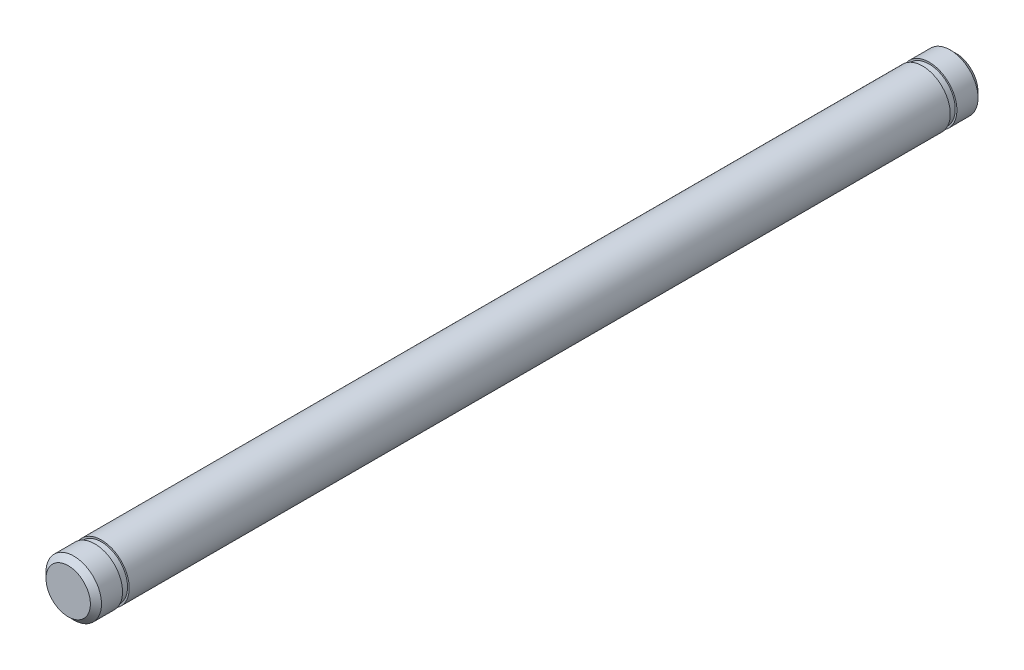
SolidWorks part; units mm, degrees
ref_plane "前视基准面" through (0, 0, 0) normal (0, 0, 1) x (1, 0, 0)
ref_plane "上视基准面" through (0, 0, 0) normal (0, 1, 0) x (1, 0, 0)
ref_plane "右视基准面" through (0, 0, 0) normal (1, 0, 0) x (0, 0, -1)
other "Configuration Table"
sketch "草图1" plane through (0, 0, 0) normal (0, 0, 1) x (1, 0, 0)
  circle A0 centre (0, 0) radius 2.5
  dimension "D1" = 5
extrude "凸台-拉伸1" add sketch "草图1" along normal blind 80
chamfer "倒角1" distance 0.5 angle 45 2 edges at (2.5, 0, 80) (2.5, 0, 0)
ref_plane "基准面1" through (0, 0, 40) normal (0, 0, 1) x (1, 0, 0)
sketch "草图2" plane through (0, 0, 0) normal (0, 0, -1) x (-1, 0, 0)
  circle A0 centre (0, 0) radius 2.5 construction
  circle A1 centre (0, 0) radius 2.5
  circle A2 centre (0, 0) radius 2.35
  dimension "D1" = 4.7
extrude "切除-拉伸1" cut sketch "草图2" along normal blind 0.6 from offset 3 offset against normal yes
mirror "镜向1" about plane through (0, 0, 40) normal (0, 0, 1) of "切除-拉伸1"
